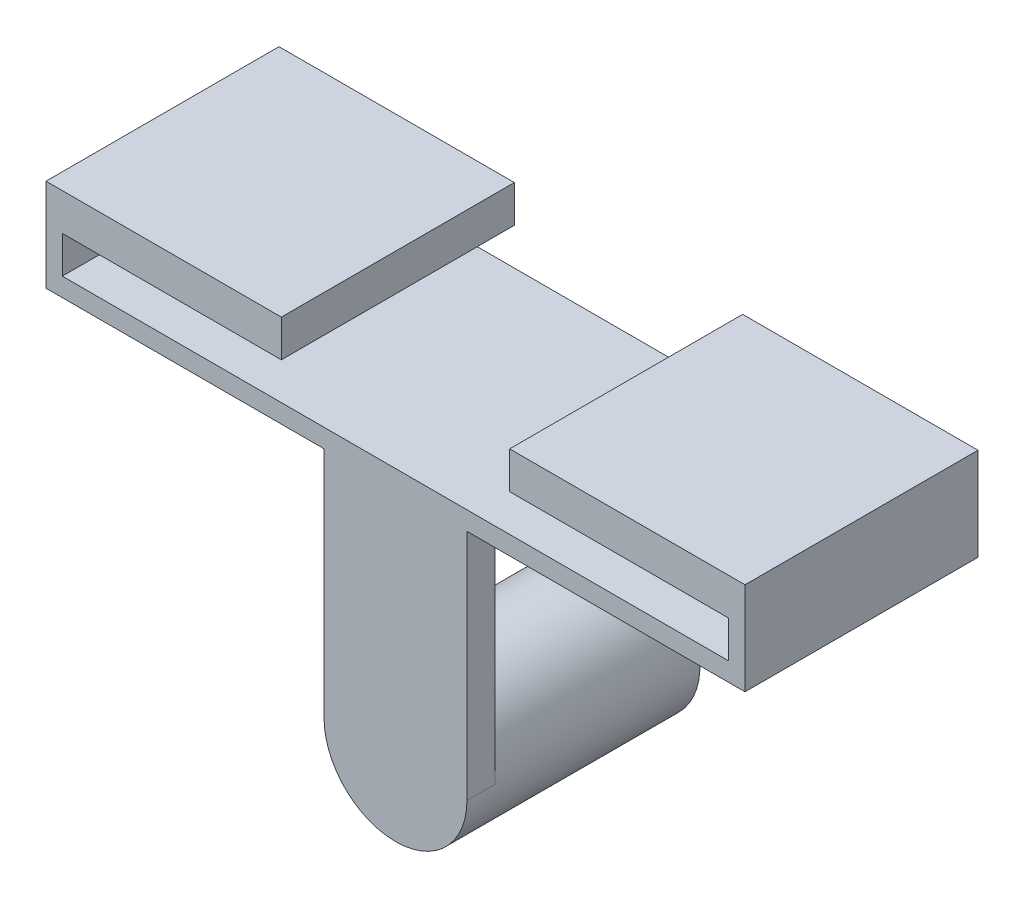
SolidWorks part; units mm, degrees
ref_plane "Front Plane" through (0, 0, 0) normal (0, 0, 1) x (1, 0, 0)
ref_plane "Top Plane" through (0, 0, 0) normal (0, 1, 0) x (1, 0, 0)
ref_plane "Right Plane" through (0, 0, 0) normal (1, 0, 0) x (0, 0, -1)
sketch "Sketch1" plane through (0, 0, 0) normal (0, 0, 1) x (1, 0, 0)
  line L0 (-38.1, 0) -> (38.1, 0)
  line L1 (38.1, 0) -> (38.1, 10.1092)
  line L3 (-12.4424, 10.1092) -> (-12.4424, 6.0706)
  line L5 (36.322, 6.0706) -> (36.322, 2.032)
  line L6 (36.322, 2.032) -> (-36.322, 2.032)
  line L7 (0, 2.032) -> (0, 0)
  line L8 (-36.322, 6.0706) -> (-36.322, 2.032)
  line L9 (-38.1, 0) -> (-38.1, 10.1092)
  line L11 (12.4424, 10.1092) -> (12.4424, 6.0706)
  line L13 (-36.322, 6.0706) -> (-12.4424, 6.0706)
  line L14 (12.4424, 6.0706) -> (36.322, 6.0706)
  line L15 (-38.1, 10.1092) -> (-12.4424, 10.1092)
  line L16 (12.4424, 10.1092) -> (38.1, 10.1092)
  dimension "D1" = 76.2
  dimension "D2" = 2.032
  dimension "D3" = 4.0386
  dimension "D4" = 1.778
  dimension "D5" = 4.0386
  dimension "D6" = 25.6576
extrude "Boss-Extrude1" add sketch "Sketch1" against normal blind 25.4 contours L11 L14 L5 L6 L8 L13 L3 L15 L9 L0 L1 L16
sketch "Sketch2" plane through (0, 0, 0) normal (0, 0, 1) x (1, 0, 0)
  line L0 (-7.7906, 0) -> (-7.7906, -25.4)
  line L1 (-7.7906, 0) -> (7.7906, 0)
  line L2 (0, 0) -> (0, -25.4)
  line L3 (-7.7906, -25.4) -> (7.7906, -25.4)
  line L4 (7.7906, 0) -> (7.7906, -25.4)
  line M6 (-38.1, 0) -> (38.1, 0)
  dimension "D1" = 25.4
extrude "Boss-Extrude2" add sketch "Sketch2" against normal blind 3.048 contours L0 L3 L2 M6 | L4 L1 L2 L3
ref_plane "Plane1" through (0, 0, 0) normal (0, 0, -1) x (-1, 0, 0)
sketch "Sketch3" plane through (0, 0, 0) normal (0, 0, -1) x (-1, 0, 0)
  line L0 (7.7906, -25.4) -> (-7.7906, -25.4) construction
  circle A0 centre (0, -25.4) radius 7.7906
  dimension "D1" = 15.5812
extrude "Boss-Extrude3" add sketch "Sketch3" along normal blind 25.4 contours A0
equation "\"F\"= 600"
equation "\"Sy\"= 40000"
equation "\"rho\"= .975"
equation "\"E\"= 10000"
equation "\"v\"= .33"
equation "\"SF\"= 4"
equation "\"L1\"= 1"
equation "\"d1\"= ( 32 * ( 2 * \"F\" ) * \"L1\" * \"SF\" ) / ( \"Sy\" * 3.14 * 2 )"
equation "\"d2\"= ( \"SF\" * 2 * \"F\" ) / ( \"Sy\" * \"L1\" )"
equation "\"h1\"= 1in"
equation "\"L2\"= 1in"
equation "\"W\"= 3in"
equation "\"h2\"= ( ( \"F\" * \"L1\" * \"SF\" * 2 * 6 ) / ( \"Sy\" * \"W\" ) ) ^ 1 / 3"
equation "\"h3\"= 1.6in"
equation "\"W2\"= ( \"F\" * \"L1\" * \"SF\" * 6 ) / ( \"h3\" ^ 2 * \"Sy\" * 2 )"
equation "\"h4\"= ( ( \"F\" * \"W2\" * \"SF\" * 6 ) / ( \"Sy\" * \"L1\" ) )"
